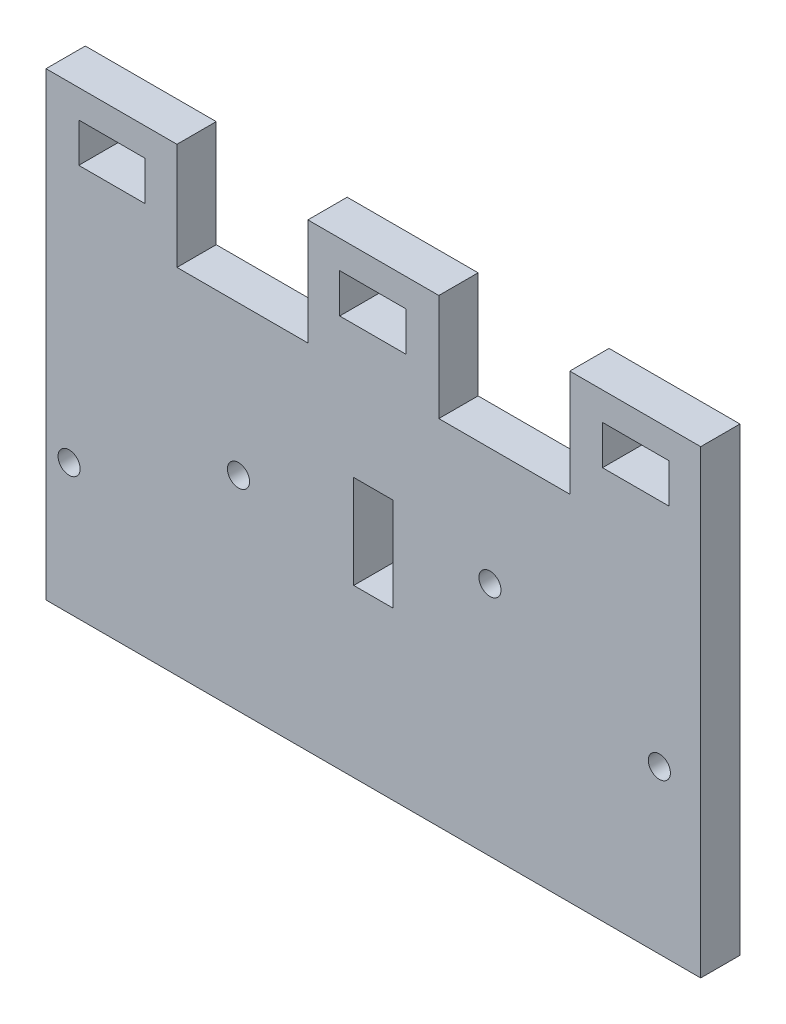
SolidWorks part; units mm, degrees
ref_plane "Front Plane" through (0, 0, 0) normal (0, 0, 1) x (1, 0, 0)
ref_plane "Top Plane" through (0, 0, 0) normal (0, 1, 0) x (1, 0, 0)
ref_plane "Right Plane" through (0, 0, 0) normal (1, 0, 0) x (0, 0, -1)
sketch "Sketch1" plane through (0, 0, 0) normal (0, 0, 1) x (1, 0, 0)
  line L1 (-39.3603, 14.4208) -> (49.5397, 14.4208)
  line L2 (-39.3603, 14.4208) -> (-39.3603, -48.0632)
  line L3 (-39.3603, -48.0632) -> (49.5397, -48.0632)
  line L4 (49.5397, 14.4208) -> (49.5397, -48.0632)
  dimension "D1" = 88.9
  dimension "D2" = 62.484
extrude "Boss-Extrude1" add sketch "Sketch1" along normal blind 5.334
sketch "Sketch2" plane through (0, 0, 5.334) normal (0, 0, 1) x (1, 0, 0)
  line L0 (49.5397, 14.4208) -> (-39.3603, 14.4208) construction
  line L1 (-21.5803, 14.4208) -> (-3.8003, 14.4208)
  line L2 (-21.5803, 14.4208) -> (-21.5803, -0.0572)
  line L3 (-21.5803, -0.0572) -> (-3.8003, -0.0572)
  line L4 (-3.8003, 14.4208) -> (-3.8003, -0.0572)
  line L5 (-21.5803, -0.0572) -> (-39.3603, -0.0572) construction
  line L6 (13.9797, 14.4208) -> (31.7597, 14.4208)
  line L7 (13.9797, 14.4208) -> (13.9797, -0.0572)
  line L8 (13.9797, -0.0572) -> (31.7597, -0.0572)
  line L9 (31.7597, 14.4208) -> (31.7597, -0.0572)
  line L10 (-39.3603, 14.4208) -> (-39.3603, -48.0632) construction
  line L11 (-3.8003, -0.0572) -> (13.9797, -0.0572) construction
  line L12 (31.7597, -0.0572) -> (49.5397, -0.0572) construction
  line L13 (49.5397, -48.0632) -> (49.5397, 14.4208) construction
  dimension "D1" = 14.478
extrude "Cut-Extrude1" cut sketch "Sketch2" against normal through all
sketch "Sketch3" plane through (0, 0, 5.334) normal (0, 0, 1) x (1, 0, 0)
  line L0 (-21.5803, 14.4208) -> (-39.3603, 14.4208) construction
  line L1 (-34.9153, 10.6108) -> (-25.8983, 10.6108)
  line L2 (-34.9153, 10.6108) -> (-34.9153, 5.2768)
  line L3 (-34.9153, 5.2768) -> (-25.8983, 5.2768)
  line L4 (-25.8983, 10.6108) -> (-25.8983, 5.2768)
  line L6 (-39.3603, 14.4208) -> (-39.3603, -48.0632) construction
  line L7 (-21.5803, 14.4208) -> (-21.5803, -0.0572) construction
  line L8 (-12.6903, -0.0572) -> (-12.6903, 17.5431) construction
  line L9 (-21.5803, -0.0572) -> (-3.8003, -0.0572) construction
  line L10 (22.8697, -0.0572) -> (22.8697, 18.5459) construction
  line L11 (13.9797, -0.0572) -> (31.7597, -0.0572) construction
  line L12 (0.5177, 10.6108) -> (0.5177, 5.2768)
  line L13 (9.5347, 5.2768) -> (0.5177, 5.2768)
  line L14 (9.5347, 10.6108) -> (9.5347, 5.2768)
  line L15 (9.5347, 10.6108) -> (0.5177, 10.6108)
  line L16 (36.2047, 10.6108) -> (45.2217, 10.6108)
  line L17 (36.2047, 10.6108) -> (36.2047, 5.2768)
  line L18 (36.2047, 5.2768) -> (45.2217, 5.2768)
  line L19 (45.2217, 10.6108) -> (45.2217, 5.2768)
  dimension "D1" = 3.81
  dimension "D2" = 5.334
  dimension "D3" = 4.445
  dimension "D4" = 4.318
extrude "Cut-Extrude2" cut sketch "Sketch3" against normal through all
sketch "Sketch5" plane through (0, 0, 5.334) normal (0, 0, 1) x (1, 0, 0)
  line L0 (5.0897, 14.4208) -> (5.0897, -48.0632) construction
  line L1 (2.4227, -12.7572) -> (7.7567, -12.7572)
  line L2 (2.4227, -12.7572) -> (2.4227, -25.4572)
  line L3 (2.4227, -25.4572) -> (7.7567, -25.4572)
  line L4 (7.7567, -12.7572) -> (7.7567, -25.4572)
  line L5 (13.9797, 14.4208) -> (-3.8003, 14.4208) construction
  line L6 (-39.3603, -48.0632) -> (49.5397, -48.0632) construction
  line L7 (13.9797, -0.0572) -> (31.7597, -0.0572) construction
  dimension "D1" = 5.334
  dimension "D2" = 12.7
  dimension "D3" = 12.7
  dimension "D4" = 2.667
extrude "Cut-Extrude3" cut sketch "Sketch5" against normal through all
sketch "Sketch6" plane through (0, 0, 5.334) normal (0, 0, 1) x (1, 0, 0)
  line L12 (13.9797, -0.0572) -> (13.9797, 14.4208)
  line L13 (13.9797, 14.4208) -> (-3.8003, 14.4208)
  line L14 (-3.8003, 14.4208) -> (-3.8003, -0.0572)
  line L15 (-3.8003, -0.0572) -> (-21.5803, -0.0572)
  line L16 (-21.5803, -0.0572) -> (-21.5803, 14.4208)
  line L17 (-21.5803, 14.4208) -> (-39.3603, 14.4208)
  line L18 (-39.3603, 14.4208) -> (-39.3603, -48.0632)
  line L19 (-39.3603, -48.0632) -> (49.5397, -48.0632)
  line L20 (49.5397, -48.0632) -> (49.5397, 14.4208)
  line L21 (49.5397, 14.4208) -> (31.7597, 14.4208)
  line L22 (31.7597, 14.4208) -> (31.7597, -0.0572)
  line L23 (31.7597, -0.0572) -> (13.9797, -0.0572)
  line L24 (13.9797, -0.0572) -> (13.9797, 14.4208)
  line L25 (13.9797, 14.4208) -> (-3.8003, 14.4208)
  line L26 (-3.8003, 14.4208) -> (-3.8003, -0.0572)
  line L27 (-3.8003, -0.0572) -> (-21.5803, -0.0572)
  line L28 (-21.5803, -0.0572) -> (-21.5803, 14.4208)
  line L29 (-21.5803, 14.4208) -> (-39.3603, 14.4208)
  line L30 (-39.3603, 14.4208) -> (-39.3603, -48.0632)
  line L31 (-39.3603, -48.0632) -> (49.5397, -48.0632)
  line L32 (49.5397, -48.0632) -> (49.5397, 14.4208)
  line L33 (49.5397, 14.4208) -> (31.7597, 14.4208)
  line L34 (31.7597, 14.4208) -> (31.7597, -0.0572)
  line L35 (31.7597, -0.0572) -> (13.9797, -0.0572)
  dimension "D1" = 0
sketch "Sketch7" plane through (0, 0, 5.334) normal (0, 0, 1) x (1, 0, 0)
  line L12 (13.9797, -0.0572) -> (13.9797, 14.4208)
  line L13 (13.9797, 14.4208) -> (-3.8003, 14.4208)
  line L14 (-3.8003, 14.4208) -> (-3.8003, -0.0572)
  line L15 (-3.8003, -0.0572) -> (-21.5803, -0.0572)
  line L16 (-21.5803, -0.0572) -> (-21.5803, 14.4208)
  line L17 (-21.5803, 14.4208) -> (-39.3603, 14.4208)
  line L18 (-39.3603, 14.4208) -> (-39.3603, -48.0632)
  line L19 (-39.3603, -48.0632) -> (49.5397, -48.0632)
  line L20 (49.5397, -48.0632) -> (49.5397, 14.4208)
  line L21 (49.5397, 14.4208) -> (31.7597, 14.4208)
  line L22 (31.7597, 14.4208) -> (31.7597, -0.0572)
  line L23 (31.7597, -0.0572) -> (13.9797, -0.0572)
  line L24 (13.9797, -0.0572) -> (13.9797, 14.4208)
  line L25 (13.9797, 14.4208) -> (-3.8003, 14.4208)
  line L26 (-3.8003, 14.4208) -> (-3.8003, -0.0572)
  line L27 (-3.8003, -0.0572) -> (-21.5803, -0.0572)
  line L28 (-21.5803, -0.0572) -> (-21.5803, 14.4208)
  line L29 (-21.5803, 14.4208) -> (-39.3603, 14.4208)
  line L30 (-39.3603, 14.4208) -> (-39.3603, -48.0632)
  line L31 (-39.3603, -48.0632) -> (49.5397, -48.0632)
  line L32 (49.5397, -48.0632) -> (49.5397, 14.4208)
  line L33 (49.5397, 14.4208) -> (31.7597, 14.4208)
  line L34 (31.7597, 14.4208) -> (31.7597, -0.0572)
  line L35 (31.7597, -0.0572) -> (13.9797, -0.0572)
  circle A0 centre (-36.2253, -30.3292) radius 1.5 construction
  circle A1 centre (-13.2253, -20.3292) radius 1.5 construction
  circle A2 centre (20.9247, -16.0112) radius 1.5 construction
  circle A3 centre (43.9247, -26.0112) radius 1.5 construction
  circle A4 centre (-36.2253, -30.3292) radius 1.5
  circle A5 centre (-13.2253, -20.3292) radius 1.5
  circle A6 centre (20.9247, -16.0112) radius 1.5
  circle A7 centre (43.9247, -26.0112) radius 1.5
  dimension "D1" = 0
extrude "Cut-Extrude4" cut sketch "Sketch7" against normal through all contours A4 | A6 | A7 | A5
equation "\"MDF\"= .21in"
equation "\"Foamcore\"= .13in"
equation "\"Gmaterial\"= \"MDF\""
equation "\"D1@Boss-Extrude1\"=\"MDF\""
equation "\"D1@Sketch2\"=2*\"MDF\"+.15"
equation "\"D2@Sketch3\"=\"MDF\""
equation "\"D1@Sketch5\"=\"MDF\""
equation "\"D4@Sketch5\"=\"MDF\"/2"
